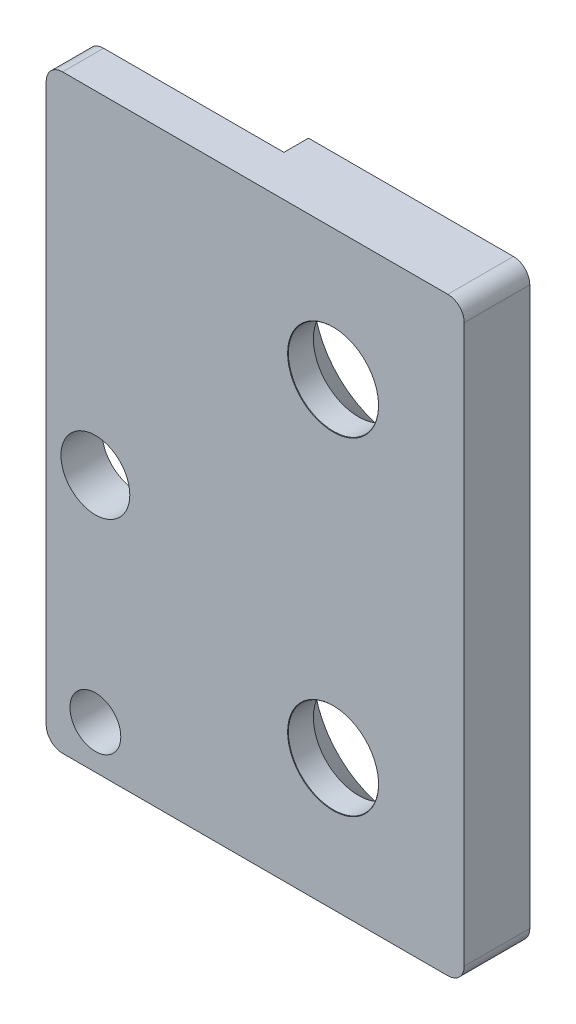
SolidWorks part; units mm, degrees
material "ABS"
ref_plane "Front Plane" through (0, 0, 0) normal (0, 0, 1) x (1, 0, 0)
ref_plane "Top Plane" through (0, 0, 0) normal (0, 1, 0) x (1, 0, 0)
ref_plane "Right Plane" through (0, 0, 0) normal (1, 0, 0) x (0, 0, -1)
sketch "Sketch1" plane through (0, 0, 0) normal (0, 0, 1) x (1, 0, 0)
  line L1 (12.75, -18) -> (-12.75, -18)
  line L2 (12.75, -18) -> (12.75, 18)
  line L3 (12.75, 18) -> (-12.75, 18)
  line L4 (-12.75, -18) -> (-12.75, 18)
  line L5 (12.75, -18) -> (-12.75, 18) construction
  line L6 (12.75, 18) -> (-12.75, -18) construction
  point P0 (0, 0)
  dimension "D1" = 36
  dimension "D2" = 25.5
extrude "Boss-Extrude1" add sketch "Sketch1" along normal blind 4
sketch "Sketch2" plane through (0, 18, 0) normal (0, 1, 0) x (1, 0, 0)
  line L0 (12.75, -4) -> (-12.75, -4) construction
  line L1 (-12.75, 0) -> (-0.75, 0)
  line L2 (-12.75, 0) -> (-12.75, -1.5)
  line L3 (-12.75, -1.5) -> (-0.75, -1.5)
  line L4 (-0.75, 0) -> (-0.75, -1.5)
  dimension "D1" = 2.5
  dimension "D2" = 12
extrude "Cut-Extrude1" cut sketch "Sketch2" against normal up to next
hole_wizard "CSK for M5 Countersunk Flat Head Screw1" positions "Sketch3" profile "Sketch5" countersink size "M5" standard "DIN" end condition up to next
sketch "Sketch3" plane through (0, 0, 0) normal (0, 0, -1) x (-1, 0, 0)
  line L0 (-12.75, 0) -> (0.75, 0) construction
  line L1 (-12.75, -18) -> (-12.75, 18) construction
  line L2 (0.75, -18) -> (0.75, 18) construction
  line L4 (-4.75, 0) -> (-4.75, 15) construction
  point P0 (-4.75, 10)
  point P2 (-4.75, -10)
  dimension "D1" = 20
  dimension "D2" = 8
sketch "Sketch5" plane through (4.75, 10, 0) normal (1, 0, 0) x (0, 1, 0)
  line L0 (0, 0) -> (0, 4)
  line L1 (0, 4) -> (2.775, 4)
  line L2 (2.75, 3.975) -> (2.75, 2.45)
  line L3 (2.75, 2.45) -> (5.2, 0)
  line L5 (5.2, 0) -> (0, 0)
  line L6 (-2.75, 2.45) -> (-5.2, 0) construction
  line L7 (2.775, 4) -> (2.75, 3.975)
  line L8 (-2.775, 4) -> (-2.75, 3.975) construction
  line L11 (0, -6.35) -> (0, 107.95) construction
  dimension "Thru Hole Dia." = 5.5
  dimension "Thru Hole Depth" = 4
  dimension "Near C'Sink Dia." = 10.4
  dimension "Near C'Sink Angle" = 90
  dimension "Far C'Sink Dia." = 5.55
  dimension "Far C'Sink Angle" = 90
hole_wizard "M3 Clearance Hole1" positions "Sketch8" profile "Sketch10" hole size "M3" standard "DIN" end condition up to next
sketch "Sketch8" plane through (0, 0, 1.5) normal (0, 0, -1) x (-1, 0, 0)
  line L2 (0.75, -18) -> (12.75, -18) construction
  line L3 (12.75, -18) -> (12.75, 18) construction
  point P0 (9.75, -15.35)
  dimension "D1" = 2.65
  dimension "D2" = 3
sketch "Sketch10" plane through (-9.75, -15.35, 1.5) normal (1, 0, 0) x (0, 1, 0)
  line L0 (0, 0) -> (0, 2.5)
  line L1 (0, 2.5) -> (1.55, 2.5)
  line L2 (1.55, 2.5) -> (1.55, 0)
  line L5 (1.55, 0) -> (0, 0)
  line L11 (0, -6.35) -> (0, 107.95) construction
  dimension "Thru Hole Dia." = 3.1
  dimension "Thru Hole Depth" = 2.5
hole_wizard "Hole1" positions "Sketch11" profile "Sketch13" legacy end condition up to next
sketch "Sketch11" plane through (0, 0, 1.5) normal (0, 0, -1) x (-1, 0, 0)
  line L2 (0.75, -18) -> (12.75, -18) construction
  line L3 (12.75, -18) -> (12.75, 18) construction
  point P0 (9.75, -2.3)
  dimension "D1" = 15.7
  dimension "D2" = 3
sketch "Sketch13" plane through (-9.75, -2.3, 1.5) normal (1, 0, 0) x (0, 1, 0)
  line L0 (0, 0) -> (0, 2.5)
  line L1 (0, 2.5) -> (2.1, 2.5)
  line L2 (2.1, 2.5) -> (2.1, 0)
  line L3 (2.1, 0) -> (0, 0)
  line L4 (0, 110) -> (0, -10) construction
  dimension "Diameter" = 4.2
  dimension "Depth" = 2.5
fillet "Fillet1" radius 1 4 edges at (-12.75, -18, 2.75) (-12.75, 18, 2.75) (12.75, 18, 2) (12.75, -18, 2)
